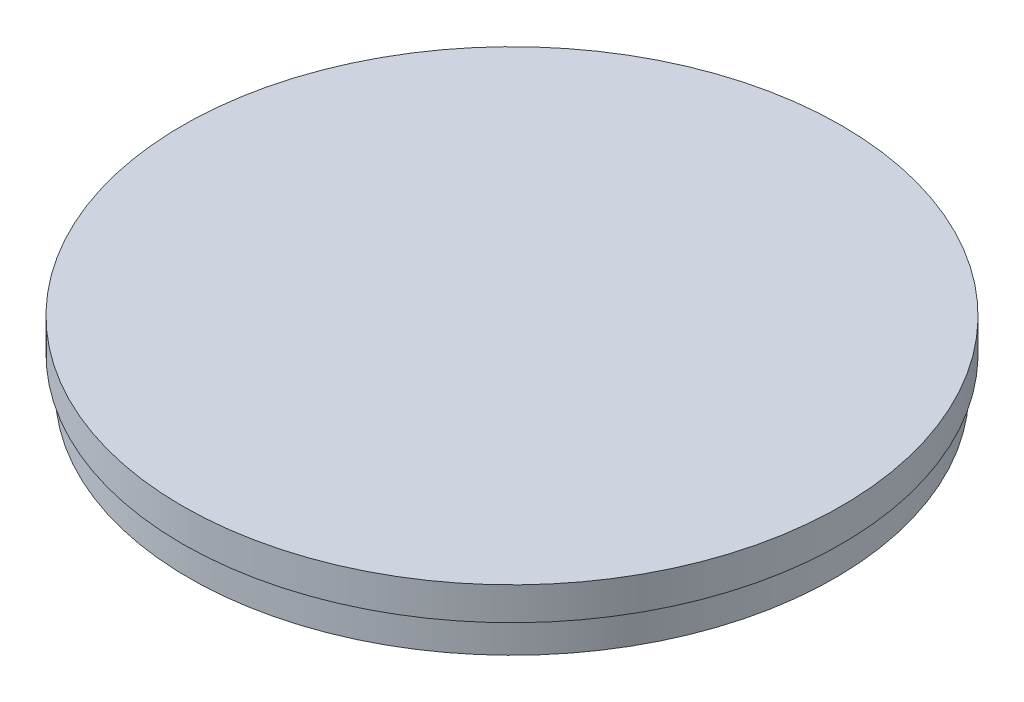
SolidWorks part; units mm, degrees
ref_plane "Front Plane" through (0, 0, 0) normal (0, 0, 1) x (1, 0, 0)
ref_plane "Top Plane" through (0, 0, 0) normal (0, 1, 0) x (1, 0, 0)
ref_plane "Right Plane" through (0, 0, 0) normal (1, 0, 0) x (0, 0, -1)
sketch "Sketch1" plane through (0, 0, 0) normal (0, 0, 1) x (1, 0, 0)
  line L0 (0, 0) -> (0, 11.938)
  line L1 (0, 11.938) -> (59.944, 11.938)
  line L2 (59.944, 11.938) -> (59.944, 5.969)
  line L3 (0, 0) -> (58.7502, 0)
  line L4 (59.944, 5.969) -> (58.7502, 5.969)
  line L5 (58.7502, 5.969) -> (58.7502, 0)
  dimension "D1" = 59.944
  dimension "D2" = 11.938
  dimension "D3" = 1.1938
  dimension "D4" = 5.969
revolve "Revolve1" add sketch "Sketch1" angle 360 about L0
